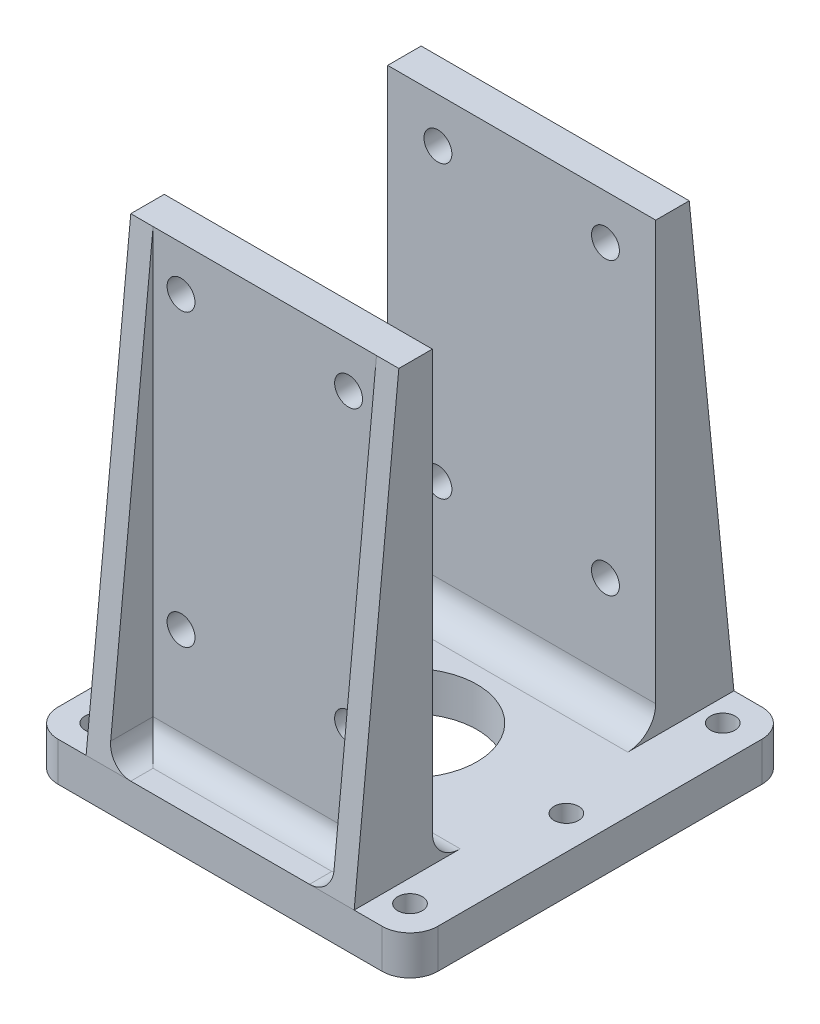
SolidWorks part; units mm, degrees
ref_plane "Front Plane" through (0, 0, 0) normal (0, 0, 1) x (1, 0, 0)
ref_plane "Top Plane" through (0, 0, 0) normal (0, 1, 0) x (1, 0, 0)
ref_plane "Right Plane" through (0, 0, 0) normal (1, 0, 0) x (0, 0, -1)
sketch "Sketch1" plane through (0, 0, 0) normal (0, 1, 0) x (1, 0, 0)
  line L1 (5, 0) -> (63, 0)
  line L2 (0, 5) -> (0, 63)
  line L3 (5, 68) -> (63, 68)
  line L4 (68, 5) -> (68, 63)
  circle A0 centre (6, 6) radius 2.2
  circle A1 centre (62, 6) radius 2.2
  circle A2 centre (62, 34) radius 2.2
  circle A3 centre (62, 62) radius 2.2
  circle A4 centre (6, 34) radius 2.2
  circle A5 centre (6, 62) radius 2.2
  circle A6 centre (34, 34) radius 12
  arc A7 (5, 0) -> (0, 5) centre (5, 5) cw
  arc A8 (63, 0) -> (68, 5) centre (63, 5) ccw
  arc A9 (63, 68) -> (68, 63) centre (63, 63) cw
  arc A10 (0, 63) -> (5, 68) centre (5, 63) cw
  point P21 (0, 0)
  point P24 (68, 0)
  point P29 (0, 68)
  dimension "D3" = 4.4
  dimension "D8" = 24
  dimension "D9" = 5
  dimension "D1" = 68
  dimension "D2" = 68
  dimension "D4" = 6
  dimension "D5" = 6
  dimension "D6" = 2
  dimension "D7" = 3
extrude "Boss-Extrude1" add sketch "Sketch1" along normal blind 7
sketch "Sketch2" plane through (0, 7, 0) normal (0, 1, 0) x (1, 0, 0)
  line L1 (10, 60) -> (58, 60)
  line L2 (10, 60) -> (10, 54)
  line L3 (10, 54) -> (58, 54)
  line L4 (58, 60) -> (58, 54)
  line L5 (10, 14) -> (58, 14)
  line L6 (10, 14) -> (10, 8)
  line L7 (10, 8) -> (58, 8)
  line L8 (58, 14) -> (58, 8)
  line L10 (5, 0) -> (63, 0) construction
  line L11 (0, 63) -> (0, 5) construction
  line L12 (68, 5) -> (68, 63) construction
  dimension "D1" = 40
  dimension "D2" = 6
  dimension "D3" = 6
  dimension "D4" = 8
  dimension "D5" = 10
  dimension "D6" = 10
  dimension "D7" = 10
  dimension "D8" = 10
extrude "Boss-Extrude2" add sketch "Sketch2" along normal blind 80
sketch "Sketch4" plane through (58, 0, 0) normal (1, 0, 0) x (0, 0, -1)
  line L0 (8, 7) -> (0, 7)
  line L1 (0, 7) -> (8, 87)
  line L2 (8, 87) -> (8, 7)
  line L3 (60, 7) -> (60, 87)
  line L4 (60, 87) -> (68, 7)
  line L5 (68, 7) -> (60, 7)
extrude "Boss-Extrude3" add sketch "Sketch4" against normal blind 48
sketch "Sketch5" plane through (0, 87, 0) normal (0, 1, 0) x (1, 0, 0)
  line L0 (58, 60) -> (10, 60) construction
  line L1 (14, 60) -> (54, 60)
  line L2 (14, 60) -> (14, 68)
  line L3 (14, 68) -> (54, 68)
  line L4 (54, 60) -> (54, 68)
  line L5 (10, 68) -> (58, 68) construction
  line L6 (10, 8) -> (58, 8) construction
  line L7 (14, 8) -> (54, 8)
  line L8 (14, 8) -> (14, 0)
  line L9 (14, 0) -> (54, 0)
  line L10 (54, 8) -> (54, 0)
  line L11 (10, 0) -> (58, 0) construction
  line L12 (10, 68) -> (10, 60) construction
  line L13 (58, 54) -> (58, 68) construction
  line L14 (10, 14) -> (10, 0) construction
  line L15 (58, 8) -> (58, 0) construction
  dimension "D1" = 4
  dimension "D2" = 4
  dimension "D3" = 4
  dimension "D4" = 4
extrude "Cut-Extrude1" cut sketch "Sketch5" against normal blind 80
sketch "Sketch6" plane through (0, 0, -8) normal (0, 0, 1) x (1, 0, 0)
  line L0 (14, 7) -> (14, 87) construction
  line L1 (54, 7) -> (54, 87) construction
  line L2 (54, 87) -> (14, 87) construction
  line L3 (54, 7) -> (14, 7) construction
  circle A0 centre (19, 79) radius 2.5
  circle A1 centre (49, 79) radius 2.5
  circle A2 centre (19, 27) radius 2.5
  circle A3 centre (49, 27) radius 2.5
  dimension "D1" = 5
  dimension "D2" = 5
  dimension "D3" = 5
  dimension "D4" = 5
  dimension "D5" = 5
  dimension "D6" = 5
  dimension "D7" = 8
  dimension "D8" = 8
  dimension "D9" = 5
  dimension "D10" = 5
  dimension "D11" = 20
  dimension "D12" = 20
extrude "Cut-Extrude2" cut sketch "Sketch6" against normal blind 80
fillet "Fillet1" radius 5 2 edges at (34, 7, -54) (34, 7, -14)
fillet "Fillet5" radius 4 6 edges at (14, 7, -4) (34, 7, -8) (54, 7, -4) (14, 7, -64) (34, 7, -60) (54, 7, -64)
